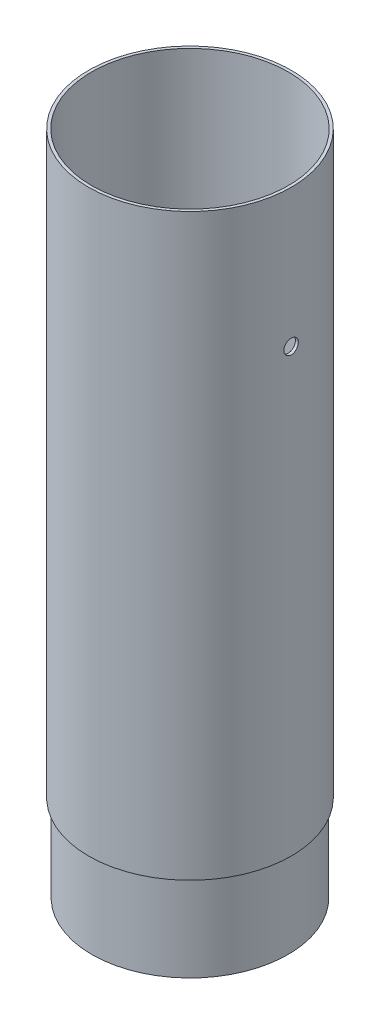
SolidWorks part; units mm, degrees
ref_plane "Front Plane" through (0, 0, 0) normal (0, 0, 1) x (1, 0, 0)
ref_plane "Top Plane" through (0, 0, 0) normal (0, 1, 0) x (1, 0, 0)
ref_plane "Right Plane" through (0, 0, 0) normal (1, 0, 0) x (0, 0, -1)
sketch "Sketch1" plane through (0, 0, 0) normal (0, 1, 0) x (1, 0, 0)
  circle A0 centre (0, 0) radius 35
  circle A1 centre (0, 0) radius 34
  dimension "D1" = 70
  dimension "D2" = 1
extrude "Boss-Extrude1" add sketch "Sketch1" along normal blind 200
sketch "Sketch2" plane through (0, 0, 0) normal (0, -1, 0) x (1, 0, 0)
  circle A0 centre (0, 0) radius 34 construction
  circle A1 centre (0, 0) radius 34
  circle A2 centre (0, 0) radius 32.9
  dimension "D1" = 1.1
extrude "Boss-Extrude2" add sketch "Sketch2" against normal blind 2
sketch "Sketch3" plane through (0, 0, 0) normal (0, -1, 0) x (1, 0, 0)
  circle A0 centre (0, 0) radius 32.9 construction
  circle A1 centre (0, 0) radius 32.9
  circle A2 centre (0, 0) radius 33.9
  dimension "D1" = 1
extrude "Boss-Extrude3" add sketch "Sketch3" along normal blind 30
sketch "Sketch4" plane through (0, 0, 0) normal (1, 0, 0) x (0, 0, -1)
  line L0 (0, 200) -> (0, 117.1673) construction
  line L1 (35, 200) -> (-35, 200) construction
  circle A0 centre (0, 152.4045) radius 2.5
  dimension "D1" = 5
extrude "Cut-Extrude1" cut sketch "Sketch4" along normal blind 40
